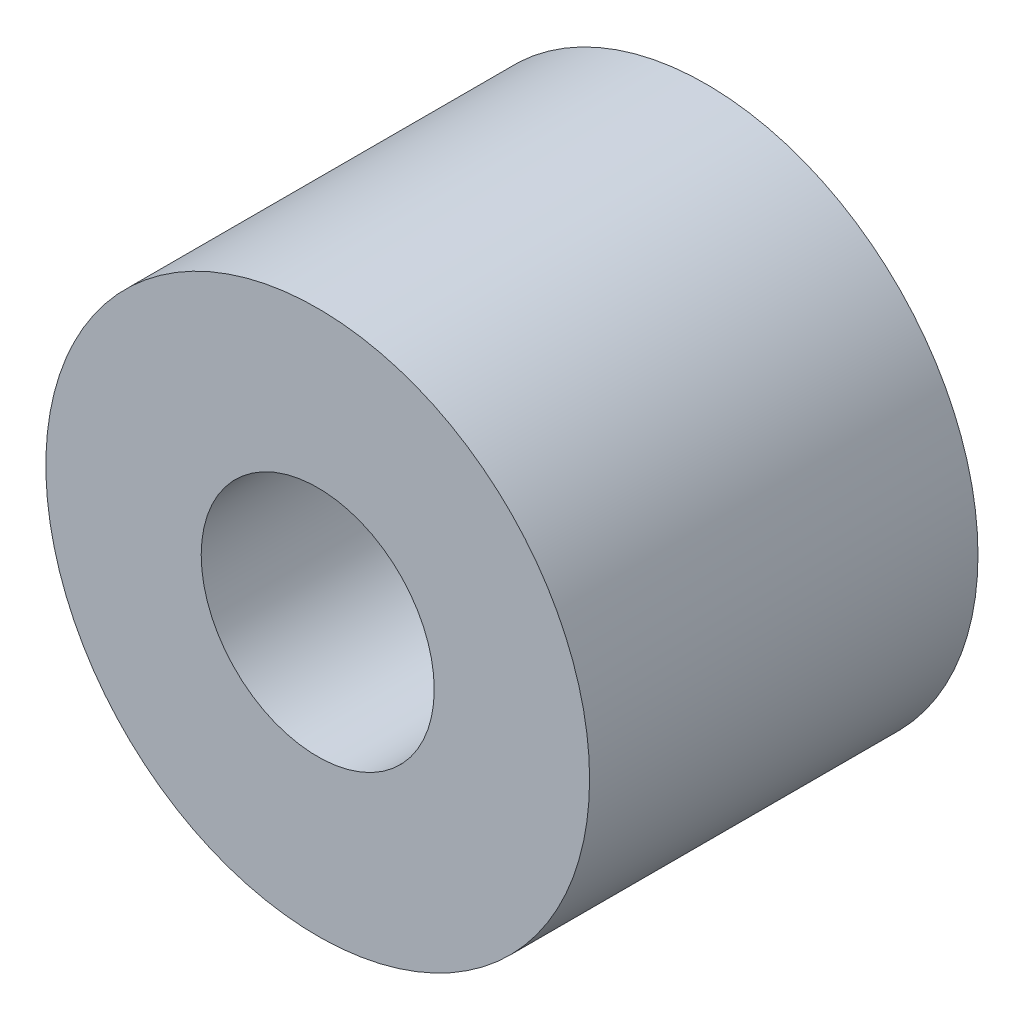
SolidWorks part; units mm, degrees
ref_plane "前视基准面" through (0, 0, 0) normal (0, 0, 1) x (1, 0, 0)
ref_plane "上视基准面" through (0, 0, 0) normal (0, 1, 0) x (1, 0, 0)
ref_plane "右视基准面" through (0, 0, 0) normal (1, 0, 0) x (0, 0, -1)
sketch "草图2" plane through (0, 0, 0) normal (0, 0, 1) x (1, 0, 0)
  circle A0 centre (0, 0) radius 1.5
  circle A1 centre (0, 0) radius 3.5
  dimension "D1" = 7
  dimension "D2" = 3
extrude "凸台-拉伸1" add sketch "草图2" along normal blind 5
